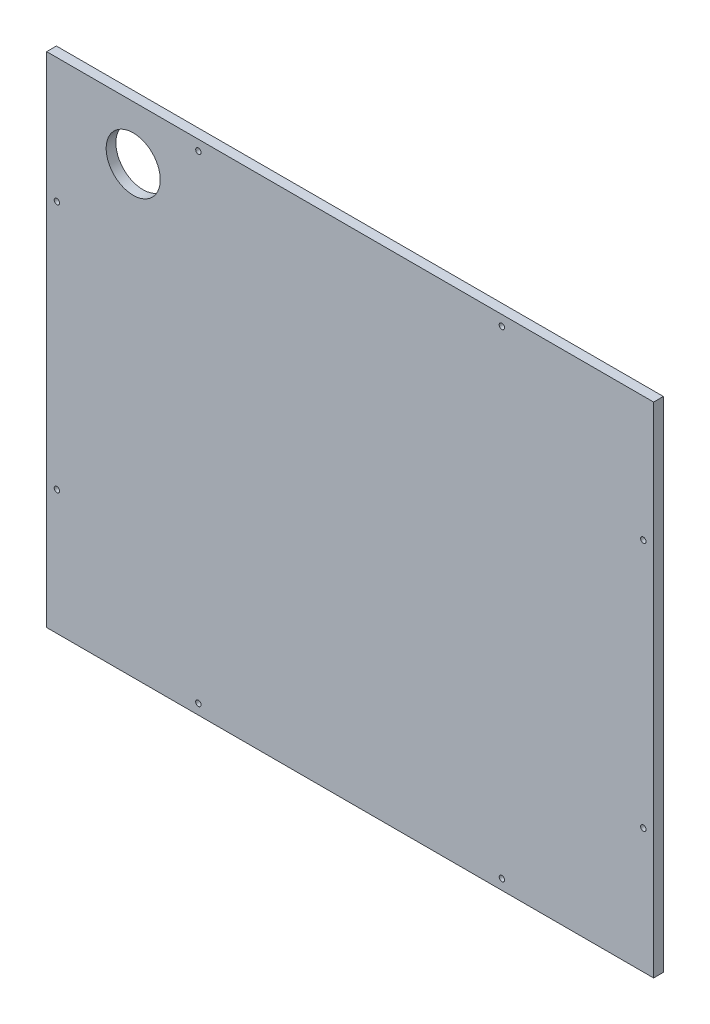
SolidWorks part; units mm, degrees
ref_plane "前视基准面" through (0, 0, 0) normal (0, 0, 1) x (1, 0, 0)
ref_plane "上视基准面" through (0, 0, 0) normal (0, 1, 0) x (1, 0, 0)
ref_plane "右视基准面" through (0, 0, 0) normal (1, 0, 0) x (0, 0, -1)
other "Configuration Table"
sketch "草图1" plane through (0, 0, 0) normal (0, 0, 1) x (1, 0, 0)
  line L0 (-280.5, 230.5) -> (280.5, 230.5) construction
  line L1 (280.5, 461) -> (-280.5, 461)
  line L2 (280.5, 461) -> (280.5, 0)
  line L3 (280.5, 0) -> (-280.5, 0)
  line L4 (-280.5, 461) -> (-280.5, 0)
  line L5 (0, 461) -> (0, 0) construction
  line L6 (-280.5, 424.8196) -> (0, 424.8196) construction
  line L7 (-239.0572, 461) -> (-239.0572, 230.5) construction
  circle A0 centre (-140.25, 451.5) radius 2.5
  circle A2 centre (-271, 345.75) radius 2.5
  circle A3 centre (271, 345.75) radius 2.5
  circle A4 centre (140.25, 451.5) radius 2.5
  circle A5 centre (271, 115.25) radius 2.5
  circle A6 centre (140.25, 9.5) radius 2.5
  circle A7 centre (-271, 115.25) radius 2.5
  circle A8 centre (-140.25, 9.5) radius 2.5
  point P4 (0, 0)
  point P16 (-140.25, 424.8196)
  point P21 (-239.0572, 345.75)
  dimension "D3" = 31.9428
  dimension "D4" = 9.5
  dimension "D5" = 5
  dimension "D6" = 9.5
  dimension "D1" = 561
  dimension "D2" = 461
extrude "凸台-拉伸1" add sketch "草图1" along normal blind 9
sketch "草图2" plane through (0, 0, 0) normal (0, 0, -1) x (-1, 0, 0)
  line L0 (280.5, 461) -> (280.5, 0) construction
  line L1 (-280.5, 461) -> (280.5, 461) construction
  circle A0 centre (200.5, 411) radius 25
  dimension "D1" = 50
  dimension "D2" = 80
  dimension "D3" = 50
extrude "切除-拉伸1" cut sketch "草图2" against normal through all both and the other way through all
